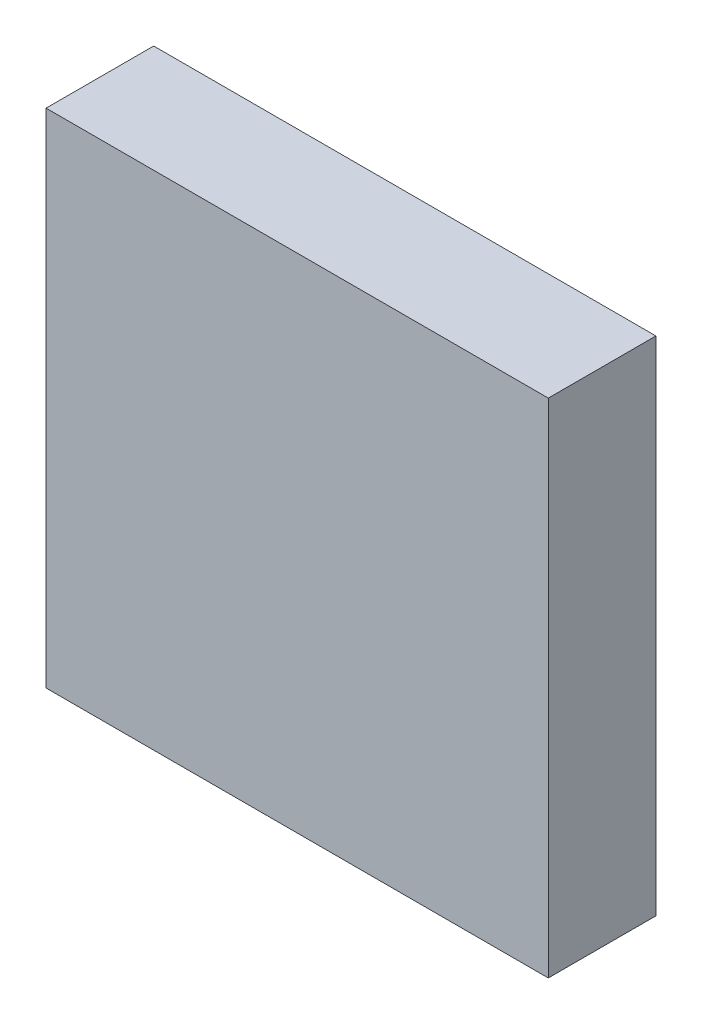
SolidWorks part; units mm, degrees
material "Pine"
ref_plane "Front Plane" through (0, 0, 0) normal (0, 0, 1) x (1, 0, 0)
ref_plane "Top Plane" through (0, 0, 0) normal (0, 1, 0) x (1, 0, 0)
ref_plane "Right Plane" through (0, 0, 0) normal (1, 0, 0) x (0, 0, -1)
sketch "Sketch1" plane through (0, 0, 0) normal (0, 0, 1) x (1, 0, 0)
  line L1 (0, 0) -> (88.9, 0)
  line L2 (0, 0) -> (0, 88.9)
  line L3 (0, 88.9) -> (88.9, 88.9)
  line L4 (88.9, 0) -> (88.9, 88.9)
  dimension "D1" = 88.9
  dimension "D2" = 88.9
extrude "Boss-Extrude1" add sketch "Sketch1" along normal blind 19.05
